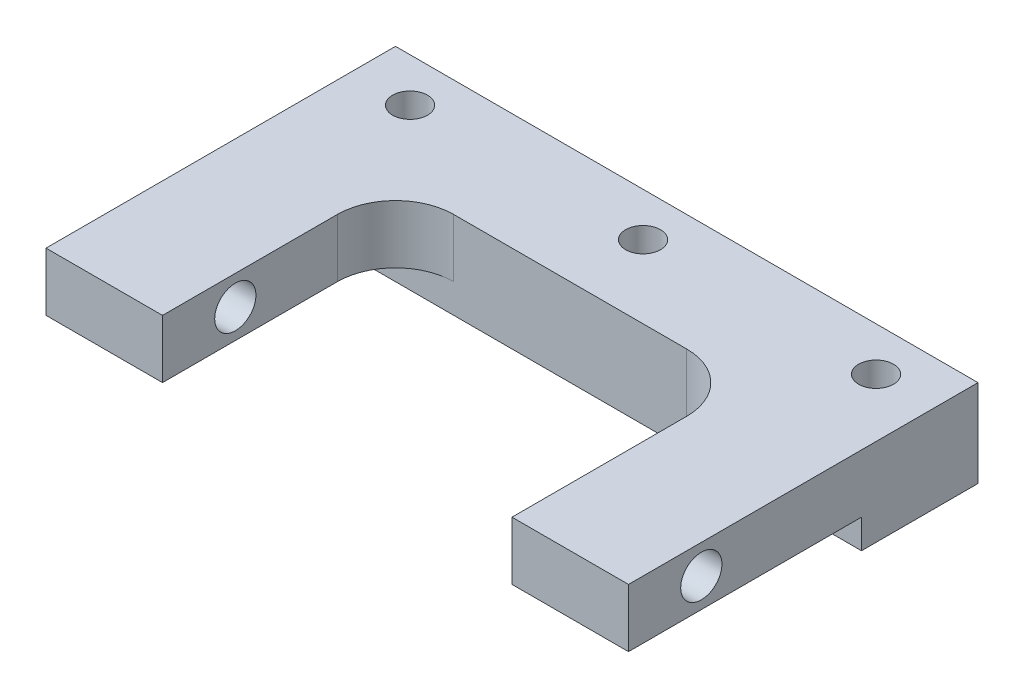
SolidWorks part; units mm, degrees
material "6061 Alloy"
ref_plane "Front" through (0, 0, 0) normal (0, 0, 1) x (1, 0, 0)
ref_plane "Top" through (0, 0, 0) normal (0, 1, 0) x (1, 0, 0)
ref_plane "Right" through (0, 0, 0) normal (1, 0, 0) x (0, 0, -1)
sketch "Sketch3" plane through (0, 0, 0) normal (0, 0, 1) x (1, 0, 0)
  line L1 (0, 0) -> (63.5, 0)
  line L2 (0, 0) -> (0, 9.525)
  line L3 (0, 9.525) -> (63.5, 9.525)
  line L4 (63.5, 0) -> (63.5, 9.525)
  dimension "D1" = 63.5
  dimension "D2" = 9.525
extrude "Boss-Extrude1" add sketch "Sketch3" along normal blind 12.7
hole_wizard "Tap Drill for #10-24 Tap1" positions "Sketch6" profile "Sketch7" hole size "#10-24" standard "ANSI Inch" end condition through all
sketch "Sketch6" plane through (0, 9.525, 0) normal (0, 1, 0) x (1, 0, 0)
  line L0 (0, -4.7625) -> (63.5, -4.7625) construction
  line L1 (0, -12.7) -> (0, 0) construction
  line L2 (63.5, -12.7) -> (63.5, 0) construction
  line L4 (63.5, -12.7) -> (0, -12.7) construction
  point P11 (6.35, -4.7625)
  point P13 (31.75, -4.7625)
  point P15 (57.15, -4.7625)
  dimension "D1" = 7.9375
  dimension "D2" = 25.4
  dimension "D3" = 25.4
sketch "Sketch7" plane through (57.15, 9.525, 4.7625) normal (1, 0, 0) x (0, 0, 1)
  line L0 (0, 0) -> (0, 9.525)
  line L1 (0, 9.525) -> (1.8986, 9.525)
  line L2 (1.8986, 9.525) -> (1.8986, 0)
  line L5 (1.8986, 0) -> (0, 0)
  line L11 (0, -6.35) -> (0, 107.95) construction
  dimension "Thru Hole Dia." = 3.7973
  dimension "Thru Hole Depth" = 9.525
hole_wizard "1/4 Clearance Hole1" [suppressed] positions "Sketch10" profile "Sketch9" hole size "1/4" standard "ANSI Inch"
sketch "Sketch10" plane through (0, 0, 12.7) normal (0, 0, 1) x (1, 0, 0)
  line L1 (19.05, 12.7) -> (19.05, 0) construction
  line L2 (63.5, 12.7) -> (0, 12.7) construction
  line L3 (0, 0) -> (63.5, 0) construction
  line L4 (31.75, 12.7) -> (31.75, 0) construction
  point P9 (31.75, 12.7)
  point P10 (19.05, 7.9375)
  point P16 (44.45, 7.9375)
  dimension "D1" = 12.7
  dimension "D2" = 7.9375
sketch "Sketch9" plane through (44.45, 7.9375, 12.7) normal (1, 0, 0) x (0, -1, 0)
  line L0 (0, 0) -> (0, 12.7)
  line L1 (0, 12.7) -> (3.5712, 12.7)
  line L2 (3.5712, 12.7) -> (3.5712, 0)
  line L5 (3.5712, 0) -> (0, 0)
  line L11 (0, -6.35) -> (0, 107.95) construction
  dimension "Thru Hole Dia." = 7.1425
  dimension "Thru Hole Depth" = 12.7
sketch "Sketch11" plane through (0, 0, 12.7) normal (0, 0, 1) x (1, 0, 0)
  line L0 (0, 0) -> (63.5, 0) construction
  line L1 (0, 9.525) -> (12.7, 9.525)
  line L2 (0, 9.525) -> (0, 3.175)
  line L3 (0, 3.175) -> (12.7, 3.175)
  line L4 (12.7, 9.525) -> (12.7, 3.175)
  line L6 (63.5, 9.525) -> (50.8, 9.525)
  line L7 (63.5, 9.525) -> (63.5, 3.175)
  line L8 (63.5, 3.175) -> (50.8, 3.175)
  line L9 (50.8, 9.525) -> (50.8, 3.175)
  dimension "D1" = 3.175
  dimension "D2" = 12.7
extrude "Boss-Extrude2" add sketch "Sketch11" along normal blind 25.4
sketch "Sketch12" plane through (0, 9.525, 0) normal (0, 1, 0) x (1, 0, 0)
  line L0 (63.5, -38.1) -> (63.5, 0) construction
  line L1 (63.5, -23.0505) -> (57.658, -23.0505)
  line L2 (63.5, -23.0505) -> (63.5, -27.7495)
  line L3 (63.5, -27.7495) -> (57.658, -27.7495)
  line L4 (57.658, -23.0505) -> (57.658, -27.7495)
  line L5 (57.658, -25.4) -> (50.8, -25.4) construction
  line L6 (50.8, -38.1) -> (50.8, -12.7) construction
  line L7 (50.8, -12.7) -> (12.7, -12.7) construction
  dimension "D1" = 12.7
  dimension "D2" = 4.699
  dimension "D3" = 5.842
extrude "Cut-Extrude1" [suppressed] cut sketch "Sketch12" against normal through all
hole_wizard "Tap Drill for #4-40 Tap1" [suppressed] positions "Sketch13" profile "Sketch14" hole size "#4-40" standard "ANSI Inch"
sketch "Sketch13" plane through (0, 0, 31.75) normal (0, 0, 1) x (1, 0, 0)
  line L0 (57.15, 9.525) -> (63.5, 3.175) construction
  line L1 (63.5, 9.525) -> (50.8, 9.525) construction
  point P8 (60.325, 6.35)
sketch "Sketch14" plane through (60.325, 6.35, 31.75) normal (1, 0, 0) x (0, -1, 0)
  line L0 (0, 0) -> (0, 19.7292)
  line L1 (0, 19.7292) -> (1.1303, 19.05)
  line L2 (1.1303, 19.05) -> (1.1303, 0)
  line L5 (1.1303, 0) -> (0, 0)
  line L10 (0, 19.7292) -> (-1.1303, 19.05) construction
  line L11 (0, -6.35) -> (0, 107.95) construction
  dimension "Hole Dia." = 2.2606
  dimension "Hole Depth" = 19.05
  dimension "Drill Angle" = 118
hole_wizard "#8 Clearance Hole1" [suppressed] positions "Sketch17" profile "Sketch16" hole size "#8" standard "ANSI Inch"
sketch "Sketch17" [suppressed] plane through (0, 0, 0) normal (-1, 0, 0) x (0, 0, 1)
  line L0 (27.7495, 9.525) -> (23.0505, 3.175) construction
  point P7 (25.4, 6.35)
sketch "Sketch16" plane through (0, 6.35, 25.4) normal (0, 1, 0) x (0, 0, 1)
  line L0 (0, 0) -> (0, 20.5266)
  line L1 (0, 20.5266) -> (2.4574, 19.05)
  line L2 (2.4574, 19.05) -> (2.4574, 0)
  line L5 (2.4574, 0) -> (0, 0)
  line L10 (0, 20.5266) -> (-2.4575, 19.05) construction
  line L11 (0, -6.35) -> (0, 107.95) construction
  dimension "Hole Dia." = 4.9149
  dimension "Hole Depth" = 19.05
  dimension "Drill Angle" = 118
hole_wizard "#8 Clearance Hole2" positions "Sketch18" profile "Sketch19" hole size "#8" standard "ANSI Inch" end condition through all
sketch "Sketch18" plane through (0, 0, 0) normal (-1, 0, 0) x (0, 0, 1)
  line L0 (38.1, 6.35) -> (30.1625, 6.35) construction
  line L1 (38.1, 9.525) -> (38.1, 3.175) construction
  line L3 (12.7, 3.175) -> (12.7, 0) construction
  point P2 (30.1625, 6.35)
  dimension "D1" = 17.4625
sketch "Sketch19" plane through (0, 6.35, 30.1625) normal (0, 1, 0) x (0, 0, 1)
  line L0 (0, 0) -> (0, 63.5)
  line L1 (0, 63.5) -> (2.2479, 63.5)
  line L2 (2.2479, 63.5) -> (2.2479, 0)
  line L5 (2.2479, 0) -> (0, 0)
  line L11 (0, -6.35) -> (0, 107.95) construction
  dimension "Thru Hole Dia." = 4.4958
  dimension "Thru Hole Depth" = 63.5
fillet "Fillet1" radius 6.35 2 edges at (12.7, 6.35, 12.7) (50.8, 6.35, 12.7)
